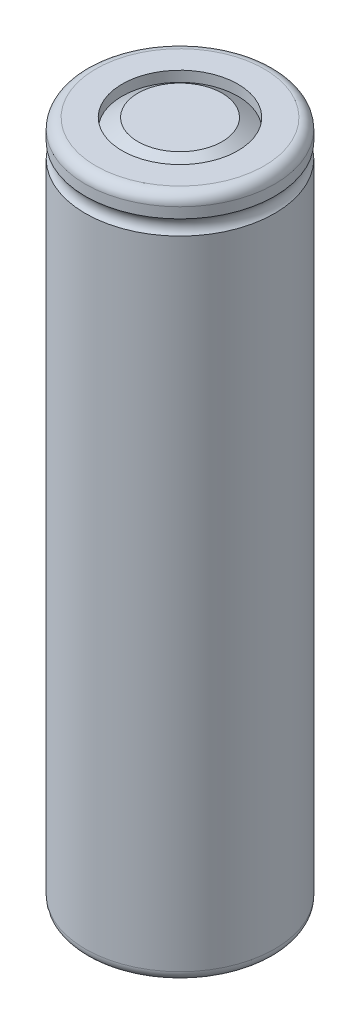
SolidWorks part; units mm, degrees
material "AISI 316 Annealed Stainless Steel Bar (SS)"
ref_plane "Front Plane" through (0, 0, 0) normal (0, 0, 1) x (1, 0, 0)
ref_plane "Top Plane" through (0, 0, 0) normal (0, 1, 0) x (1, 0, 0)
ref_plane "Right Plane" through (0, 0, 0) normal (1, 0, 0) x (0, 0, -1)
sketch "Sketch2" plane through (0, 0, 0) normal (0, 0, 1) x (1, 0, 0)
  line L0 (0, 0) -> (9, 0)
  line L1 (9, 0) -> (9, 61.5858)
  line L2 (9, 61.5858) -> (9.7071, 62.2929) construction
  line L3 (9.7071, 62.2929) -> (9, 63) construction
  line L4 (0, 0) -> (0, 50000) construction
  line L5 (9, 63) -> (9, 65)
  line L6 (9, 65) -> (5.5, 65)
  line L7 (5.5, 65) -> (5.5, 64)
  line L8 (5.5, 64) -> (4, 65)
  line L9 (4, 65) -> (0, 65)
  line L10 (0, 65) -> (0, 0)
  arc A0 (9, 63) -> (9, 61.5858) centre (9.7071, 62.2929) ccw
  dimension "D1" = 65
  dimension "D3" = 1
  dimension "D2" = 18
  dimension "D4" = 2
  dimension "D5" = 3.5
  dimension "D6" = 1
  dimension "D7" = 8
revolve "Revolve1" add sketch "Sketch2" angle 360 about L4
fillet "Fillet2" radius 1 2 edges at (0, 0, -9) (0, 65, -9)
